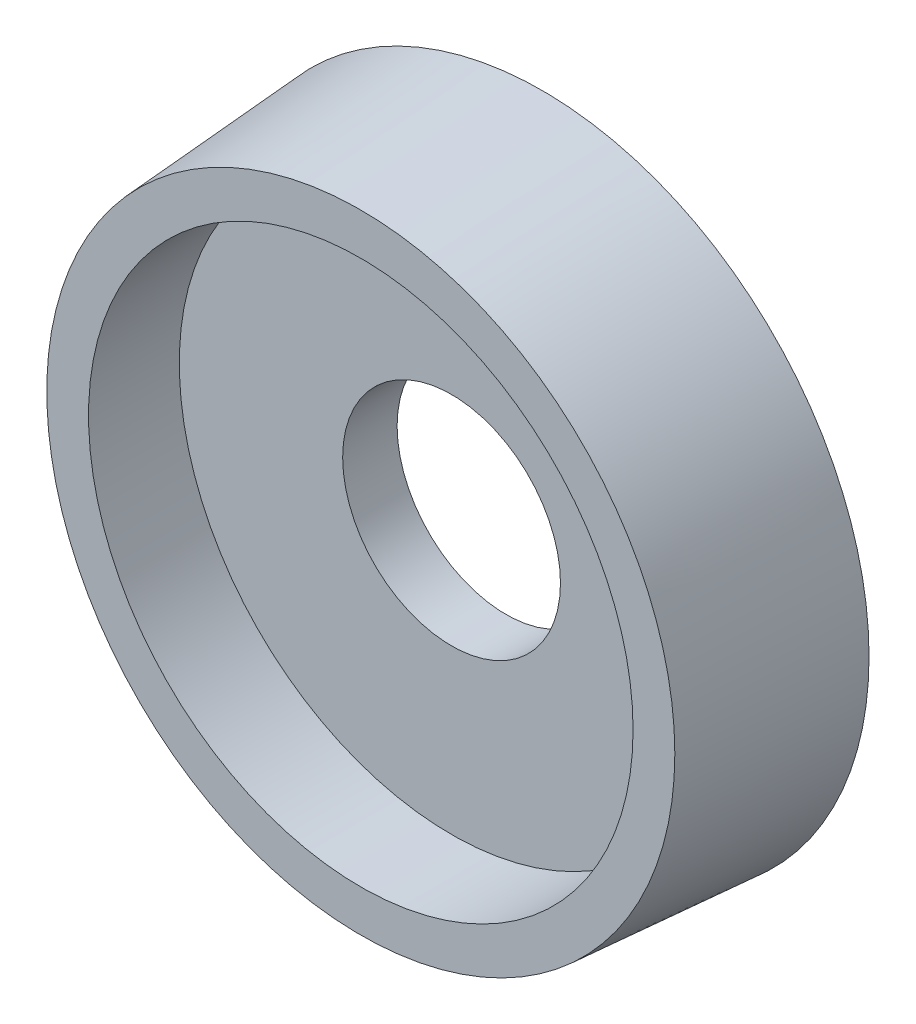
SolidWorks part; units mm, degrees
ref_plane "Спереди" through (0, 0, 0) normal (0, 0, 1) x (1, 0, 0)
ref_plane "Сверху" through (0, 0, 0) normal (0, 1, 0) x (1, 0, 0)
ref_plane "Справа" through (0, 0, 0) normal (1, 0, 0) x (0, 0, -1)
sketch "Эскиз1" plane through (0, 0, 0) normal (0, 0, 1) x (1, 0, 0)
  circle A0 centre (0, 0) radius 9
  dimension "D1" = 18
extrude "Бобышка-Вытянуть1" add sketch "Эскиз1" along normal blind 5 draft 4 contours A0
sketch "Эскиз3" plane through (0, 0, 0) normal (0, 0, -1) x (-1, 0, 0)
  circle A0 centre (0, 0) radius 5
  dimension "D1" = 10
extrude "Вырез-Вытянуть1" cut sketch "Эскиз3" against normal blind 1
sketch "Эскиз4" plane through (0, 0, 5) normal (0, 0, 1) x (1, 0, 0)
  circle A0 centre (0, 0) radius 7.5
  dimension "D1" = 15
extrude "Вырез-Вытянуть2" cut sketch "Эскиз4" against normal blind 2.5
sketch "Эскиз5" plane through (0, 0, 2.5) normal (0, 0, 1) x (1, 0, 0)
  circle A0 centre (0, 0) radius 3
  dimension "D1" = 6
extrude "Вырез-Вытянуть3" cut sketch "Эскиз5" against normal through all both and the other way through all
